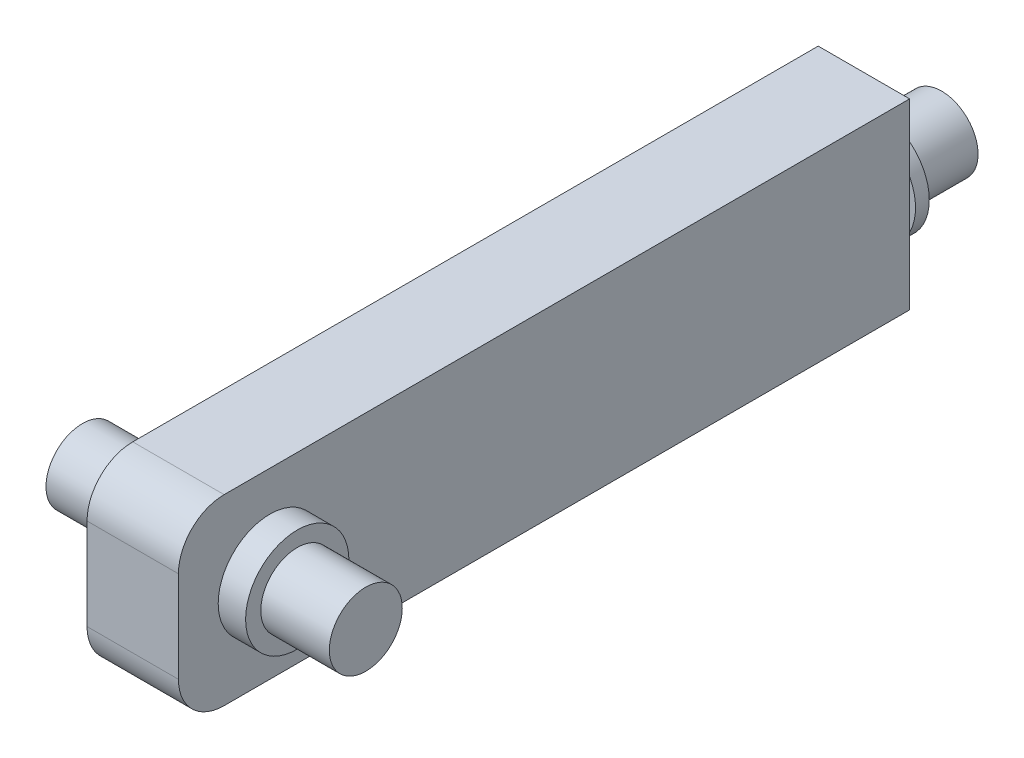
SolidWorks part; units mm, degrees
ref_plane "Front Plane" through (0, 0, 0) normal (0, 0, 1) x (1, 0, 0)
ref_plane "Top Plane" through (0, 0, 0) normal (0, 1, 0) x (1, 0, 0)
ref_plane "Right Plane" through (0, 0, 0) normal (1, 0, 0) x (0, 0, -1)
sketch "Sketch1" plane through (0, 0, 0) normal (0, 1, 0) x (1, 0, 0)
  line L0 (0, 0) -> (10, 0)
  line L1 (10, 0) -> (10, 80)
  line L2 (0, 0) -> (0, 80)
  line L3 (0, 80) -> (10, 80)
  dimension "D1" = 10
  dimension "D2" = 80
  dimension "D3" = 80
extrude "Boss-Extrude1" add sketch "Sketch1" along normal blind 20
sketch "Sketch2" plane through (10, 0, 0) normal (1, 0, 0) x (0, 0, -1)
  line L0 (0, 20) -> (0, 0) construction
  circle A0 centre (10, 10) radius 5.65
  dimension "D1" = 10
  dimension "D3" = 11.3
  dimension "D2" = 10
fillet "Fillet1" radius 5 2 edges at (5, 0, 0) (5, 20, 0)
sketch "Sketch3" plane through (0, 0, -80) normal (0, 0, -1) x (-1, 0, 0)
  line L1 (0, 0) -> (-10, 0) construction
  circle A0 centre (-5, 10) radius 3.99
  dimension "D1" = 5
  dimension "D3" = 7.98
  dimension "D2" = 10
extrude "Boss-Extrude2" add sketch "Sketch3" along normal blind 8.5
sketch "Sketch4" plane through (0, 0, -80) normal (0, 0, -1) x (-1, 0, 0)
  line L0 (-5, 6.01) -> (-5, 10) construction
  circle A0 centre (-5, 10) radius 5.65
  circle A1 centre (-5, 10) radius 3.99 construction
  dimension "D1" = 0
  dimension "D3" = 11.3
  dimension "D2" = 0
extrude "Boss-Extrude3" add sketch "Sketch4" along normal blind 1.5
extrude "Boss-Extrude4" add sketch "Sketch2" along normal blind 3
sketch "Sketch6" plane through (13, 0, 0) normal (1, 0, 0) x (0, 0, -1)
  line L0 (0, 0) -> (10, 0) construction
  line L1 (0, 0) -> (80, 0) construction
  line L2 (10, 0) -> (10, 10) construction
  circle A0 centre (10, 10) radius 3.99
  dimension "D2" = 7.98
  dimension "D1" = 10
extrude "Boss-Extrude5" add sketch "Sketch6" along normal blind 7.5
sketch "Sketch7" plane through (0, 0, 0) normal (-1, 0, 0) x (0, 0, 1)
  line L0 (0, 0) -> (-10, 0) construction
  line L1 (0, 0) -> (-80, 0) construction
  line L2 (-10, 0) -> (-10, 10) construction
  circle A0 centre (-10, 10) radius 5.65
  dimension "D3" = 11.3
  dimension "D1" = 10
  dimension "D2" = 10
extrude "Boss-Extrude6" add sketch "Sketch7" along normal blind 3 contours A0
sketch "Sketch9" plane through (-3, 0, 0) normal (-1, 0, 0) x (0, 0, 1)
  line L0 (0, 0) -> (-10, 0) construction
  line L1 (0, 0) -> (-80, 0) construction
  line L2 (-10, 0) -> (-10, 10) construction
  circle A0 centre (-10, 10) radius 3.99
  dimension "D2" = 7.98
  dimension "D1" = 10
extrude "Boss-Extrude7" add sketch "Sketch9" along normal blind 7.5
